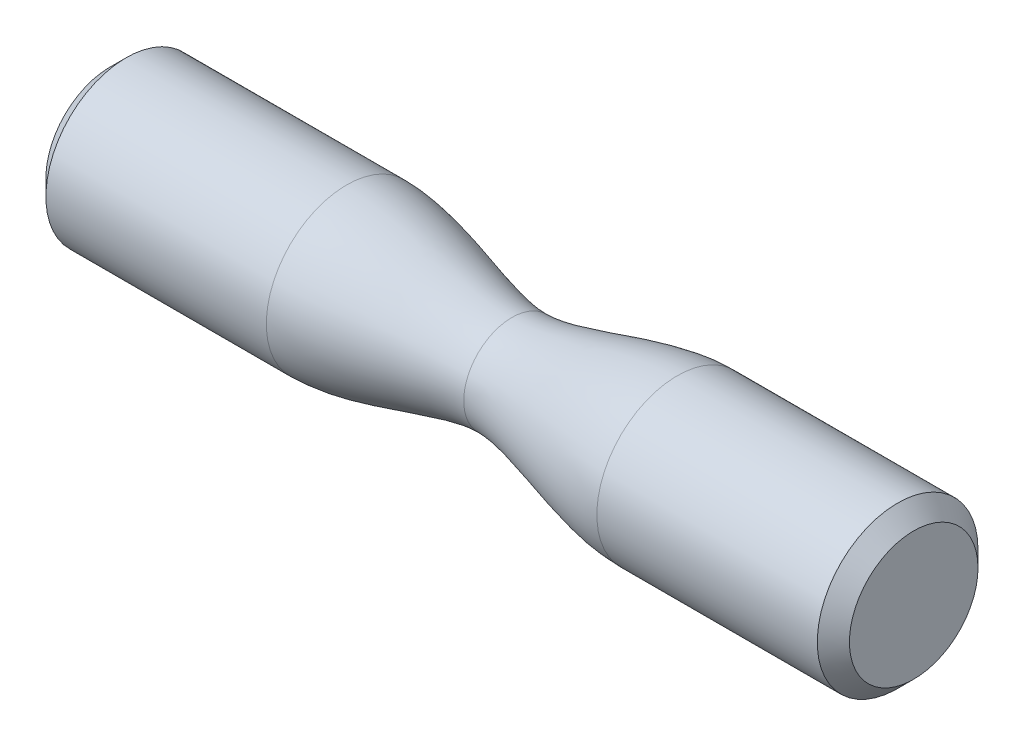
SolidWorks part; units mm, degrees
material "Alloy Steel"
ref_plane "Front" through (0, 0, 0) normal (0, 0, 1) x (1, 0, 0)
ref_plane "Top" through (0, 0, 0) normal (0, 1, 0) x (1, 0, 0)
ref_plane "Right" through (0, 0, 0) normal (1, 0, 0) x (0, 0, -1)
sketch "Sketch1" plane through (0, 0, 0) normal (0, 0, 1) x (1, 0, 0)
  line L0 (-7.9375, 0) -> (7.9375, 0) construction
  line L1 (7.9375, 1.5875) -> (7.9375, -1.5875) construction
  line L2 (-7.9375, 1.5875) -> (-7.9375, -1.5875) construction
  dimension "Length" = 15.875
  dimension "Diameter" = 3.175
sketch "Sketch2" plane through (0, 0, 0) normal (1, 0, 0) x (0, 0, -1)
  circle A0 centre (0, 0) radius 1.5875
extrude "Extrude1" add sketch "Sketch2" against normal up to vertex (7.9375 mm away) and the other way up to vertex (7.9375 mm away) up to point (-7.9375, 1.5875, 0) other way up to point (7.9375, 1.5875, 0)
chamfer "Chamfer1" distance 0.3175 angle 45 2 edges at (7.9375, 0, -1.5875) (-7.9375, 0, -1.5875)
sketch "Sketch3" plane through (0, 0, 0) normal (0, 0, 1) x (1, 0, 0)
  line L0 (0, 1.5875) -> (0, -1.5875) construction
  line L1 (7.62, 1.5875) -> (-7.62, 1.5875) construction
  line L2 (-7.62, -1.5875) -> (7.62, -1.5875) construction
  line L3 (7.9375, 0) -> (-7.9375, 0) construction
  line L4 (7.9375, -1.27) -> (7.9375, 1.27) construction
  line L5 (-7.9375, 1.27) -> (-7.9375, -1.27) construction
  line L6 (1.7736, 1.5875) -> (4.8523, 1.5875) construction
  line L7 (-0.4426, 0.9525) -> (0.4426, 0.9525) construction
  line L8 (3.2651, 1.5875) -> (-3.2651, 1.5875)
  spline S0 degree 3 poles (3.2651, 1.5875) (2.1144, 1.5875) (0.8785, 0.9525) (0, 0.9525) knots 0 0 0 0 1 1 1 1
  spline S1 degree 3 poles (-3.2651, 1.5875) (-2.1144, 1.5875) (-0.8785, 0.9525) (0, 0.9525) knots 0 0 0 0 1 1 1 1
  dimension "D1" = 0.635
revolve "Cut-Revolve1" cut sketch "Sketch3" angle 360 about L3
equation "\"D1@Chamfer1\" = \"Diameter@Sketch1\"*.1"
